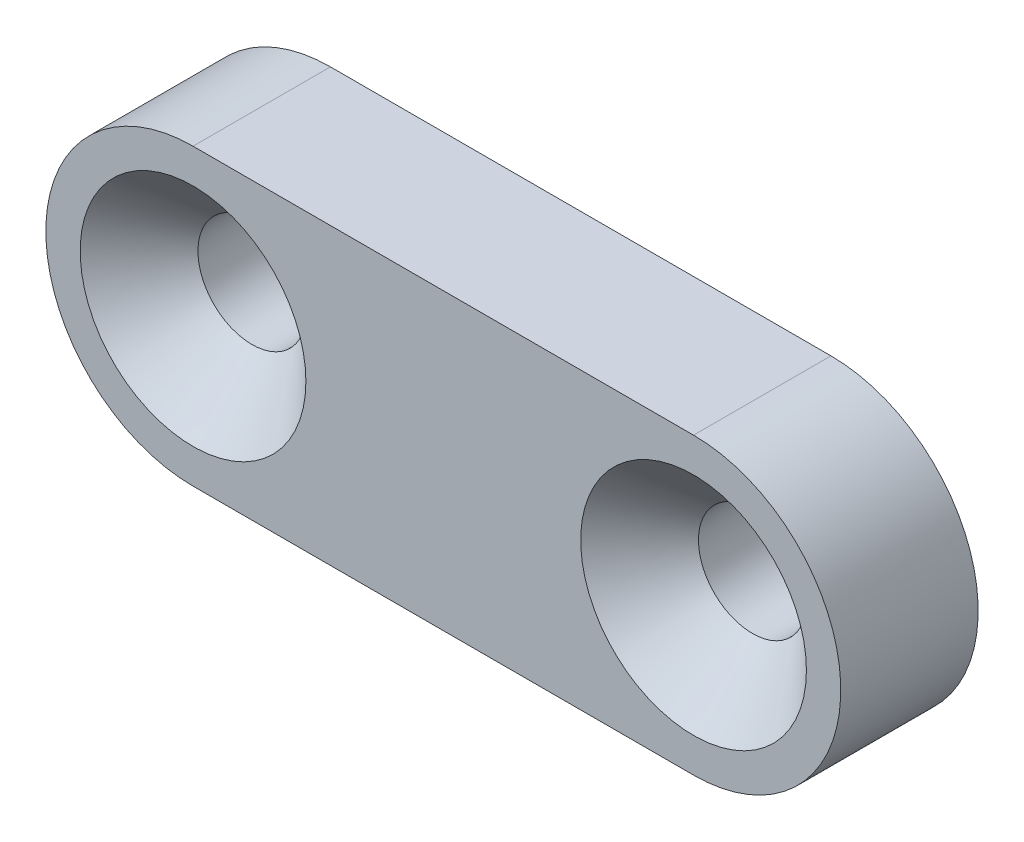
SolidWorks part; units mm, degrees
ref_plane "Plan de face" through (0, 0, 0) normal (0, 0, 1) x (1, 0, 0)
ref_plane "Plan de dessus" through (0, 0, 0) normal (0, 1, 0) x (1, 0, 0)
ref_plane "Plan de droite" through (0, 0, 0) normal (1, 0, 0) x (0, 0, -1)
sketch "Esquisse1" plane through (0, 0, 0) normal (0, 0, 1) x (1, 0, 0)
  line L1 (0, -7.5) -> (25.5, -7.5)
  line L2 (0, -7.5) -> (0, 7.5) construction
  line L3 (0, 7.5) -> (25.5, 7.5)
  line L4 (25.5, -7.5) -> (25.5, 7.5) construction
  arc A0 (0, 7.5) -> (0, -7.5) centre (0, 0) ccw
  arc A1 (25.5, 7.5) -> (25.5, -7.5) centre (25.5, 0) cw
  circle A2 centre (0, 0) radius 2.75
  circle A3 centre (25.5, 0) radius 2.75
  dimension "D3" = 5.5
  dimension "D1" = 25.5
  dimension "D2" = 15
extrude "Boss.-Extru.1" add sketch "Esquisse1" along normal blind 7
chamfer "Chanfrein1" distance 3 angle 45 2 edges at (28.25, 0, 7) (2.75, 0, 7)
